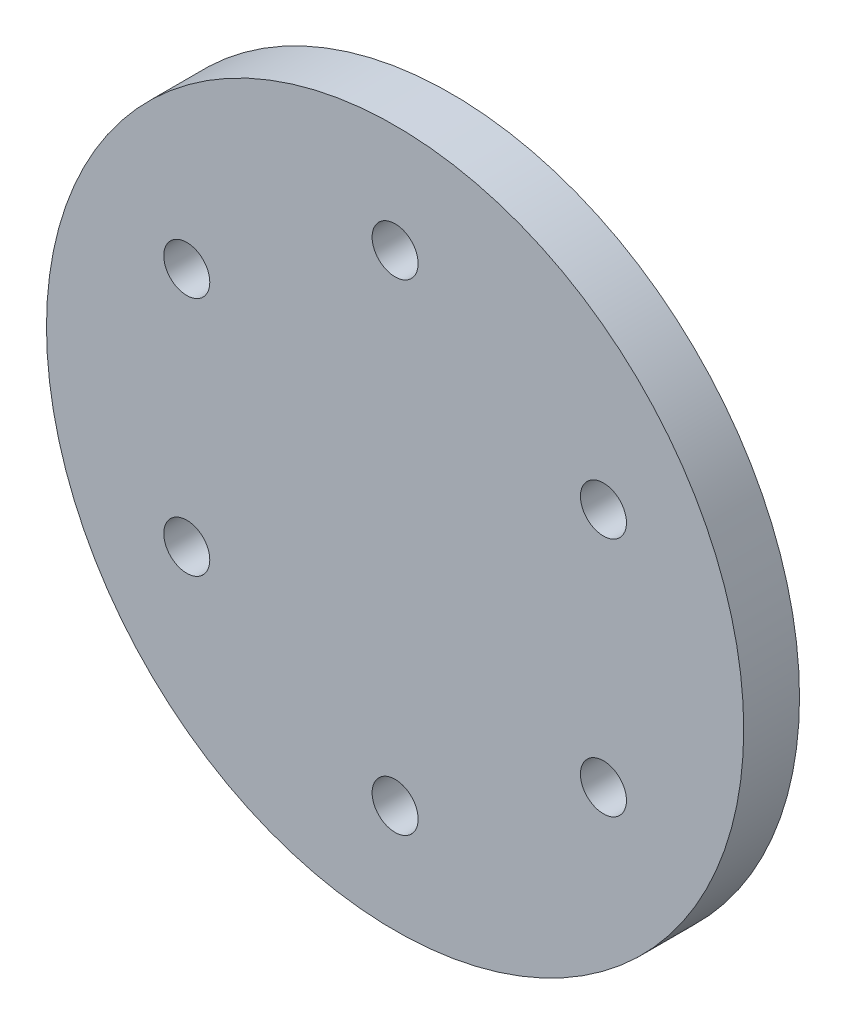
SolidWorks part; units mm, degrees
ref_plane "前视基准面" through (0, 0, 0) normal (0, 0, 1) x (1, 0, 0)
ref_plane "上视基准面" through (0, 0, 0) normal (0, 1, 0) x (1, 0, 0)
ref_plane "右视基准面" through (0, 0, 0) normal (1, 0, 0) x (0, 0, -1)
other "Configuration Table"
sketch "草图1" plane through (0, 0, 0) normal (0, 0, 1) x (1, 0, 0)
  circle A0 centre (0, 0) radius 17.25 construction
  circle A1 centre (0, 17.25) radius 1.65
  circle A2 centre (14.9389, 8.625) radius 1.65
  circle A3 centre (14.9389, -8.625) radius 1.65
  circle A4 centre (0, -17.25) radius 1.65
  circle A5 centre (-14.9389, -8.625) radius 1.65
  circle A6 centre (-14.9389, 8.625) radius 1.65
  circle A7 centre (0, 0) radius 25
  point P17 (0, 0)
  dimension "D1" = 34.5
  dimension "D2" = 3.3
  dimension "D4" = 50
  dimension "D3" = 6
extrude "凸台-拉伸1" add sketch "草图1" along normal blind 4
